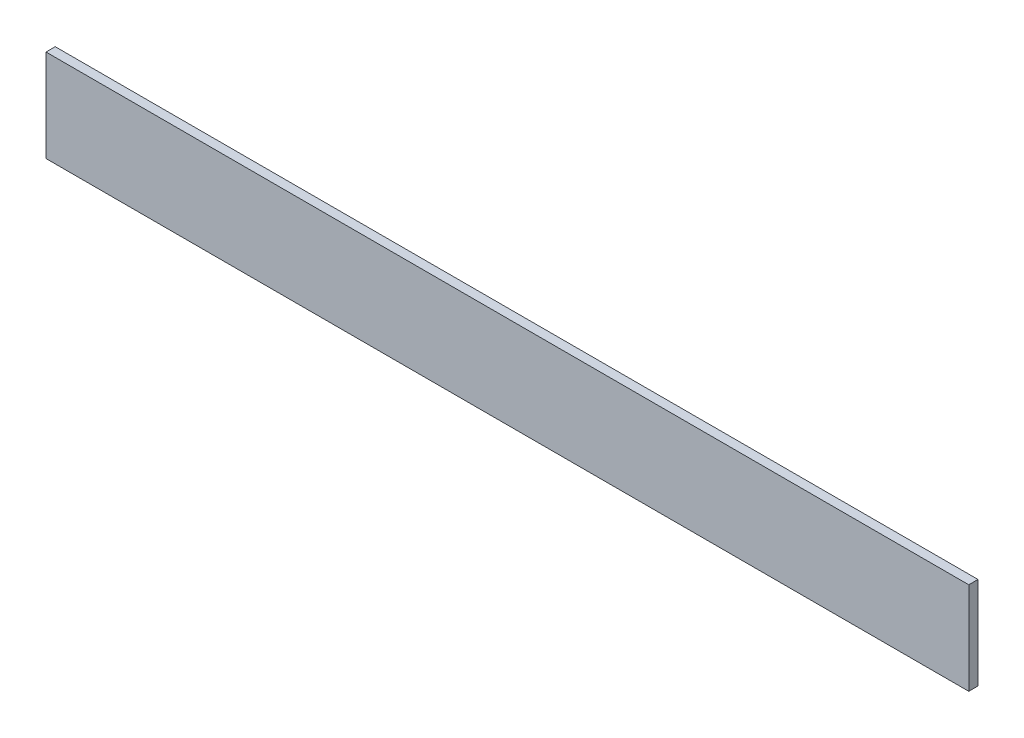
SolidWorks part; units mm, degrees
material "Acrylic (Medium-high impact)"
ref_plane "Front Plane" through (0, 0, 0) normal (0, 0, 1) x (1, 0, 0)
ref_plane "Top Plane" through (0, 0, 0) normal (0, 1, 0) x (1, 0, 0)
ref_plane "Right Plane" through (0, 0, 0) normal (1, 0, 0) x (0, 0, -1)
sketch "Sketch1" plane through (0, 0, 0) normal (1, 0, 0) x (0, -1, 0)
  line L1 (5, 0) -> (55, 0)
  line L5 (55, 5) -> (25, 5)
  line L9 (15, 5) -> (5, 5)
  line L12 (15, 5) -> (25, 5)
  line L13 (5, 5) -> (5, 0)
  line L14 (55, 5) -> (55, 0)
  dimension "D3" = 5
extrude "Boss-Extrude1" add sketch "Sketch1" along normal blind 500
